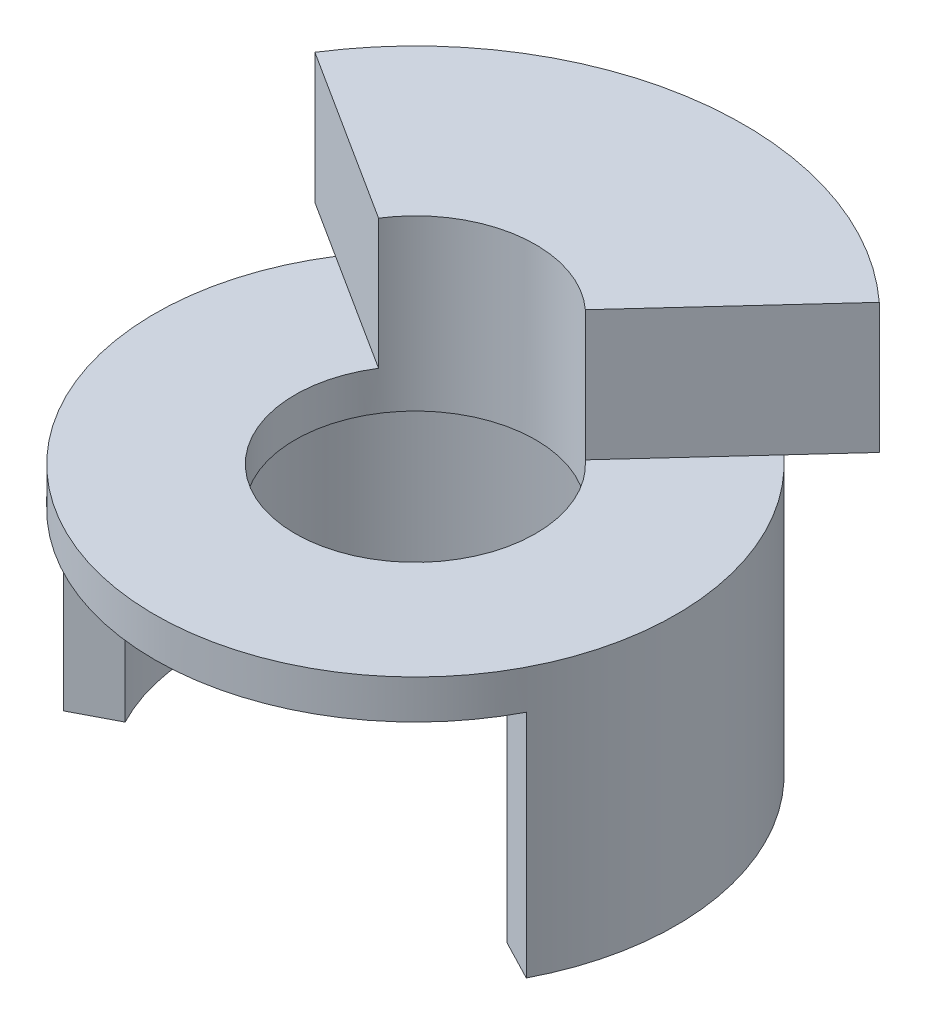
SolidWorks part; units mm, degrees
material "Zinc AC41A Alloy, As Cast"
ref_plane "Front" through (0, 0, 0) normal (0, 0, 1) x (1, 0, 0)
ref_plane "Top" through (0, 0, 0) normal (0, 1, 0) x (1, 0, 0)
ref_plane "Right" through (0, 0, 0) normal (1, 0, 0) x (0, 0, -1)
sketch "Sketch1" plane through (0, 0, 0) normal (0, 1, 0) x (1, 0, 0)
  circle A0 centre (0, 0) radius 5.0927
  dimension "D1" = 10.1854
extrude "Boss-Extrude1" add sketch "Sketch1" along normal blind 5.2578
sketch "Sketch2" plane through (0, 5.2578, 0) normal (0, 1, 0) x (1, 0, 0)
  circle A0 centre (0, 0) radius 2.3495
  dimension "D1" = 4.699
extrude "Cut-Extrude1" cut sketch "Sketch2" against normal through all
sketch "Sketch3" plane through (0, 0, 0) normal (0, -1, 0) x (1, 0, 0)
  circle A3 centre (0, 0) radius 4.2037
  dimension "D1" = 8.4074
extrude "Cut-Extrude2" cut sketch "Sketch3" against normal offset from surface (4.4958 mm away) 0.762 up to face at (0, 5.2578, 2.3495)
sketch "Sketch5" plane through (0, 0, 0) normal (0, -1, 0) x (1, 0, 0)
  line L0 (0, 0) -> (4.5173, 2.3515)
  line L1 (0, 0) -> (-4.5173, 2.3515)
  circle A0 centre (0, 0) radius 5.0927 construction
  arc A1 (-4.5173, 2.3515) -> (4.5173, 2.3515) centre (0, 0) cw
  point P5 (0, 0)
  point P7 (0, 0)
  point P8 (0, 5.0927)
  dimension "D1" = 125
extrude "Cut-Extrude3" cut sketch "Sketch5" against normal up to surface (4.4958 mm away) up to face at (0, 4.4958, 4.2037)
sketch "Sketch4" plane through (0, 5.2578, 0) normal (0, 1, 0) x (1, 0, 0)
  line L0 (0, 0) -> (4.3329, 4.7285) construction
  line L2 (4.3329, 4.7285) -> (1.5873, 1.7322)
  line L3 (-5.4091, 3.446) -> (-1.9815, 1.2624)
  line L4 (-4.5173, -2.3515) -> (-3.7287, -1.9411) construction
  line L5 (0, 0) -> (-5.4091, 3.446) construction
  arc A0 (-1.9815, 1.2624) -> (1.5873, 1.7322) centre (0, 0) cw
  circle A1 centre (0, 0) radius 2.3495 construction
  arc A4 (4.3329, 4.7285) -> (-5.4091, 3.446) centre (0, 0) ccw
  dimension "D2" = 4.064
  dimension "D1" = 100
  dimension "D3" = 60
extrude "Boss-Extrude2" add sketch "Sketch4" along normal blind 2.54
